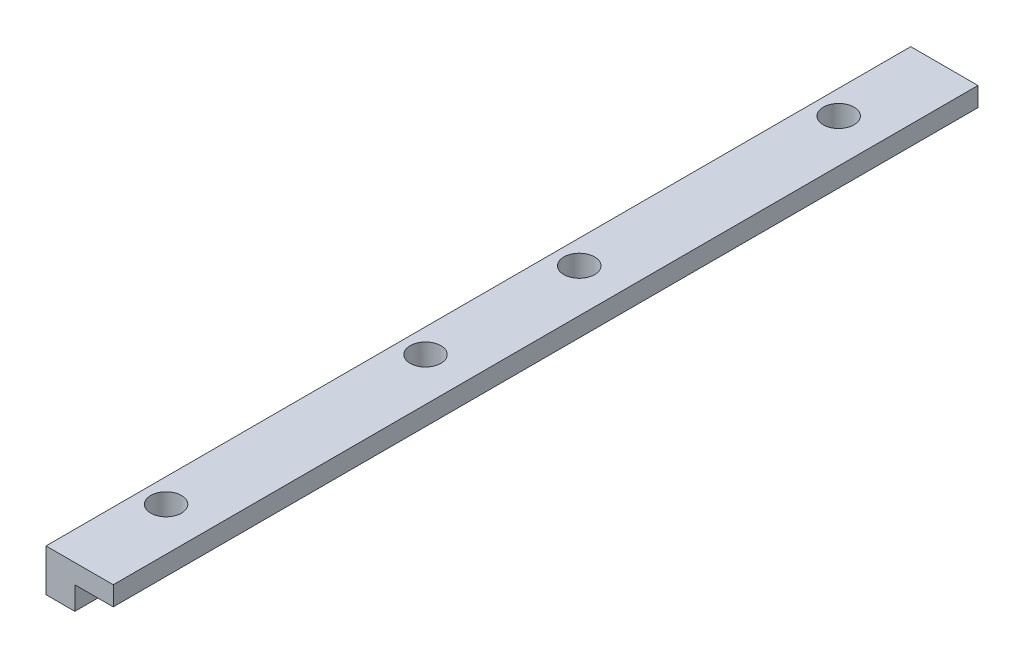
SolidWorks part; units mm, degrees
ref_plane "前视基准面" through (0, 0, 0) normal (0, 0, 1) x (1, 0, 0)
ref_plane "上视基准面" through (0, 0, 0) normal (0, 1, 0) x (1, 0, 0)
ref_plane "右视基准面" through (0, 0, 0) normal (1, 0, 0) x (0, 0, -1)
sketch "草图1" plane through (0, 0, 0) normal (0, 0, 1) x (1, 0, 0)
  line L0 (3, 0) -> (3, 2.4)
  line L1 (0, 0) -> (3, 0)
  line L2 (0, 0) -> (0, 4.4)
  line L3 (0, 4.4) -> (7, 4.4)
  line L4 (7, 4.4) -> (7, 2.4)
  line L5 (3, 2.4) -> (7, 2.4)
  dimension "D1" = 4.4
  dimension "D2" = 7
  dimension "D3" = 3
  dimension "D4" = 2.4
extrude "凸台-拉伸1" add sketch "草图1" along normal blind 90
sketch "草图2" plane through (0, 4.4, 0) normal (0, 1, 0) x (1, 0, 0)
  line L0 (2.5, 0) -> (2.5, -90) construction
  line L1 (7, 0) -> (0, 0) construction
  line L2 (7, -90) -> (0, -90) construction
  line L3 (0, -90) -> (0, 0) construction
  line L4 (0, -45) -> (34.1629, -45) construction
  circle A0 centre (2.5, -37) radius 1.6
  circle A1 centre (2.5, -10) radius 1.6
  circle A2 centre (2.5, -80) radius 1.6
  circle A3 centre (2.5, -53) radius 1.6
  dimension "D2" = 3.2
  dimension "D3" = 3.2
  dimension "D1" = 2.5
  dimension "D4" = 16
  dimension "D5" = 70
extrude "切除-拉伸1" cut sketch "草图2" against normal through all
